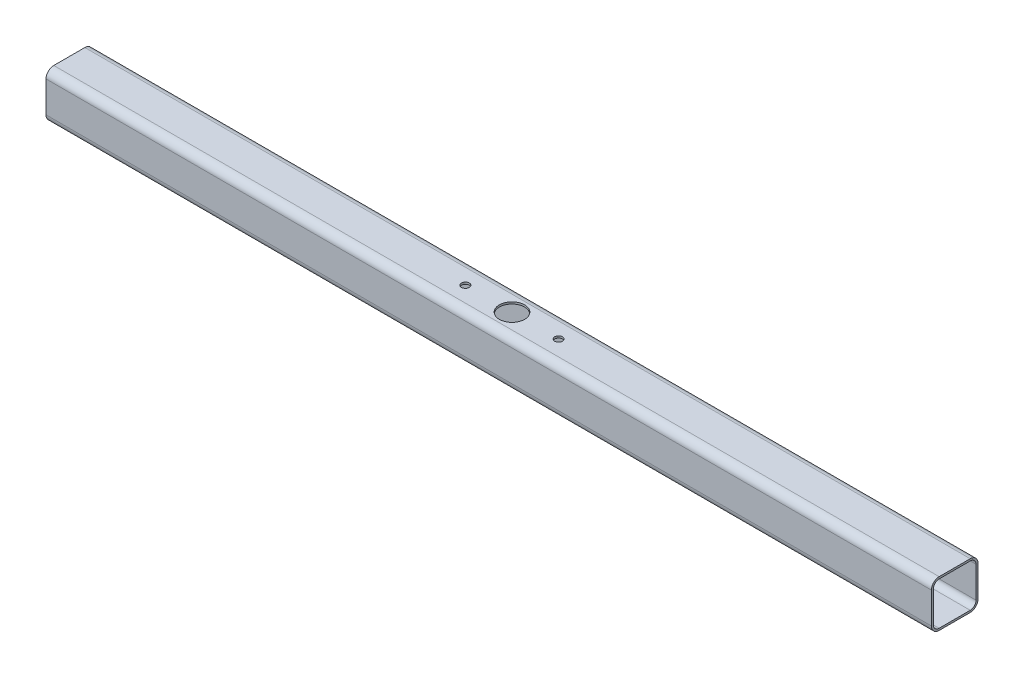
SolidWorks part; units mm, degrees
material "Plain Carbon Steel"
ref_plane "Front Plane" through (0, 0, 0) normal (0, 0, 1) x (1, 0, 0)
ref_plane "Top Plane" through (0, 0, 0) normal (0, 1, 0) x (1, 0, 0)
ref_plane "Right Plane" through (0, 0, 0) normal (1, 0, 0) x (0, 0, -1)
sketch "Sketch1" plane through (0, 0, 0) normal (0, 0, 1) x (1, 0, 0)
  line L0 (0, 0) -> (-1447.8, 0)
  dimension "D1" = 1447.8
other "Structural Member1"
ref_plane "Plane1" through (0, 0, 0) normal (-1, 0, 0) x (0, -1, 0)
sketch "Sketch11" plane through (0, 0, 0) normal (-1, 0, 0) x (0, -1, 0)
  line L0 (-25.4, -34.925) -> (25.4, -34.925)
  line L1 (-34.925, -25.4) -> (-34.925, 25.4)
  line L2 (25.4, 34.925) -> (-25.4, 34.925)
  line L3 (34.925, 25.4) -> (34.925, -25.4)
  line L4 (-25.4, -38.1) -> (25.4, -38.1)
  line L5 (-38.1, -25.4) -> (-38.1, 25.4)
  line L6 (25.4, 38.1) -> (-25.4, 38.1)
  line L7 (38.1, 25.4) -> (38.1, -25.4)
  line L8 (0, 0) -> (34.925, 0) construction
  line L9 (0, 0) -> (0, 34.925) construction
  arc A0 (38.1, 25.4) -> (25.4, 38.1) centre (25.4, 25.4) ccw
  arc A1 (25.4, -38.1) -> (38.1, -25.4) centre (25.4, -25.4) ccw
  arc A2 (-38.1, -25.4) -> (-25.4, -38.1) centre (-25.4, -25.4) ccw
  arc A3 (-25.4, 38.1) -> (-38.1, 25.4) centre (-25.4, 25.4) ccw
  arc A4 (-25.4, 34.925) -> (-34.925, 25.4) centre (-25.4, 25.4) ccw
  arc A5 (34.925, 25.4) -> (25.4, 34.925) centre (25.4, 25.4) ccw
  arc A6 (25.4, -34.925) -> (34.925, -25.4) centre (25.4, -25.4) ccw
  arc A7 (-34.925, -25.4) -> (-25.4, -34.925) centre (-25.4, -25.4) ccw
  point P3 (0, 38.1)
  point P4 (38.1, 0)
  point P5 (0, -38.1)
  point P6 (-38.1, 0)
  point P7 (-38.1, 38.1)
  point P8 (-38.1, -38.1)
  point P33 (0, 0)
  point P35 (38.1, -38.1)
  point P36 (38.1, 38.1)
  point P37 (0, 0)
  dimension "D1" = 12.7
  dimension "Thickness" = 3.175
  dimension "V_leg" = 76.2
sketch "Sketch12" plane through (0, 38.1, 0) normal (0, 1, 0) x (1, 0, 0)
  line L0 (-1447.8, 0) -> (-723.9, 0) construction
  line L1 (-1447.8, -25.4) -> (-1447.8, 25.4) construction
  circle A0 centre (-723.9, 0) radius 20.6375
  dimension "D2" = 41.275
  dimension "D1" = 723.9
extrude "Cut-Extrude1" cut sketch "Sketch12" against normal through all
sketch "Sketch13" plane through (0, 38.1, 0) normal (0, 1, 0) x (1, 0, 0)
  line L0 (-800.1, 0) -> (-723.9, 0) construction
  line L1 (-723.9, 0) -> (-647.7, 0) construction
  point P0 (-800.1, 0)
  point P1 (-647.7, 0)
  dimension "D1" = 152.4
hole_wizard "1/2 (0.5) Diameter Hole1" positions "3DSketch1" profile "Sketch15" hole size "1/2" standard "ANSI Inch"
sketch3d "3DSketch1"
  point P0 (-800.1, 38.1, 0)
  point P3 (-647.7, 38.1, 0)
sketch "Sketch15" plane through (-800.1, 38.1, 0) normal (1, 0, 0) x (0, 0, 1)
  line L0 (0, 0) -> (0, 29.2155)
  line L1 (0, 29.2155) -> (6.35, 25.4)
  line L2 (6.35, 25.4) -> (6.35, 0)
  line L5 (6.35, 0) -> (0, 0)
  line L10 (0, 29.2155) -> (-6.35, 25.4) construction
  line L11 (0, -6.35) -> (0, 107.95) construction
  dimension "Hole Dia." = 12.7
  dimension "Hole Depth" = 25.4
  dimension "Drill Angle" = 118
